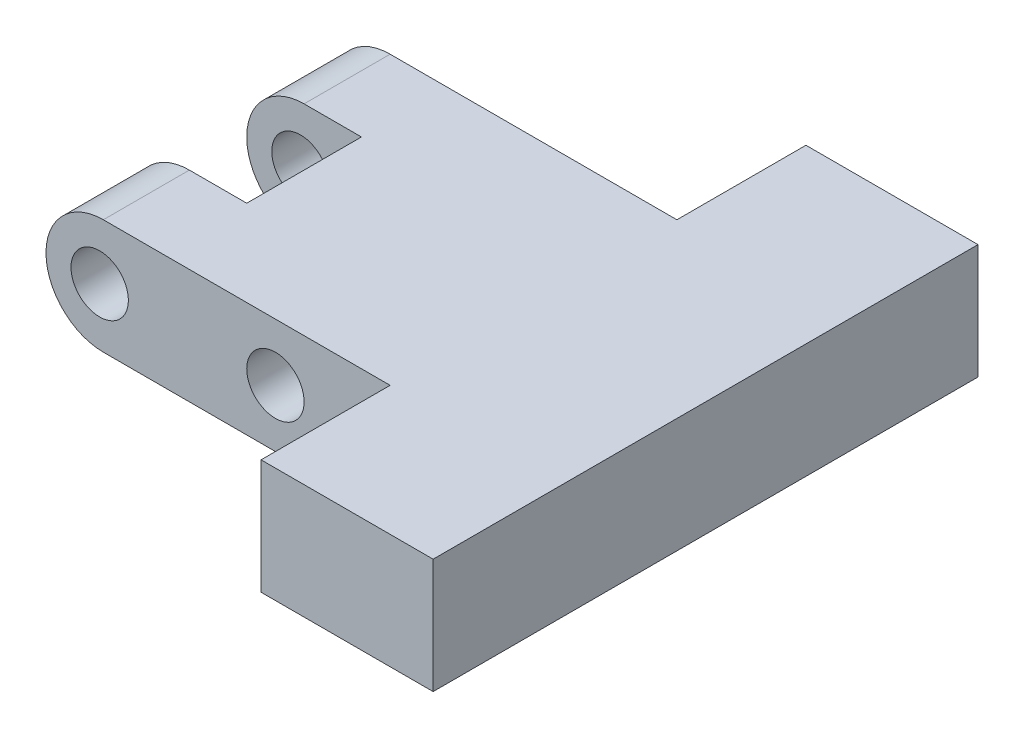
SolidWorks part; units mm, degrees
ref_plane "Front Plane" through (0, 0, 0) normal (0, 0, 1) x (1, 0, 0)
ref_plane "Top Plane" through (0, 0, 0) normal (0, 1, 0) x (1, 0, 0)
ref_plane "Right Plane" through (0, 0, 0) normal (1, 0, 0) x (0, 0, -1)
sketch "Sketch1" plane through (0, 0, 0) normal (0, 1, 0) x (1, 0, 0)
  line L1 (0, 0) -> (6, 0)
  line L2 (0, 0) -> (0, 19)
  line L3 (0, 19) -> (6, 19)
  line L4 (6, 0) -> (6, 19)
  line L5 (0, 14.5) -> (-8, 14.5)
  line L6 (0, 14.5) -> (0, 4.5)
  line L7 (0, 4.5) -> (-8, 4.5)
  line L8 (-8, 14.5) -> (-8, 4.5)
  dimension "D1" = 6
  dimension "D2" = 19
  dimension "D3" = 10
  dimension "D4" = 8
  dimension "D5" = 4.5
extrude "Boss-Extrude1" add sketch "Sketch1" along normal blind 4 contours L1 L4 L3 L2 | L5 L8 L7 L2
ref_plane "Plane1" through (0, 0, -4.5) normal (0, 0, 1) x (1, 0, 0)
sketch "Sketch2" plane through (0, 0, -4.5) normal (0, 0, 1) x (1, 0, 0)
  line L1 (-8, 0) -> (-10, 0)
  line L2 (-8, 0) -> (-8, 4)
  line L3 (-8, 4) -> (-10, 4)
  arc A0 (-10, 0) -> (-10, 4) centre (-10, 2) cw
  dimension "D1" = 2
extrude "Boss-Extrude2" add sketch "Sketch2" against normal blind 3
ref_plane "Plane2" through (0, 0, -14.5) normal (0, 0, -1) x (-1, 0, 0)
sketch "Sketch5" plane through (0, 0, -14.5) normal (0, 0, -1) x (-1, 0, 0)
  line L0 (8, 4) -> (10, 4)
  line L1 (10, 0) -> (8, 0)
  line L2 (10, 0) -> (8, 0) construction
  line L6 (8, 4) -> (8, 0)
  line L7 (8, 0) -> (10, 0)
  line L8 (10, 4) -> (8, 4)
  line L9 (8, 4) -> (8, 0)
  arc A0 (10, 0) -> (10, 4) centre (10, 2) ccw construction
  arc A1 (10, 4) -> (10, 0) centre (10, 2) cw
  arc A3 (10, 0) -> (10, 4) centre (10, 2) ccw
  dimension "D1" = 0
extrude "Boss-Extrude3" add sketch "Sketch5" against normal blind 3
sketch "Sketch6" plane through (0, 0, -14.5) normal (0, 0, -1) x (-1, 0, 0)
  line L0 (0, 4) -> (10, 4) construction
  circle A0 centre (10.128, 2) radius 1
  dimension "D1" = 2
  dimension "D2" = 2
extrude "Cut-Extrude1" cut sketch "Sketch6" against normal blind 14
sketch "Sketch7" plane through (0, 0, -14.5) normal (0, 0, -1) x (-1, 0, 0)
  line L0 (0, 0) -> (10, 0) construction
  circle A0 centre (4, 2) radius 1
  arc A1 (10, 0) -> (10, 4) centre (10, 2) ccw construction
  point P7 (12, 2)
  dimension "D1" = 2
  dimension "D3" = 8
  dimension "D2" = 2
extrude "Cut-Extrude2" cut sketch "Sketch7" against normal blind 14
